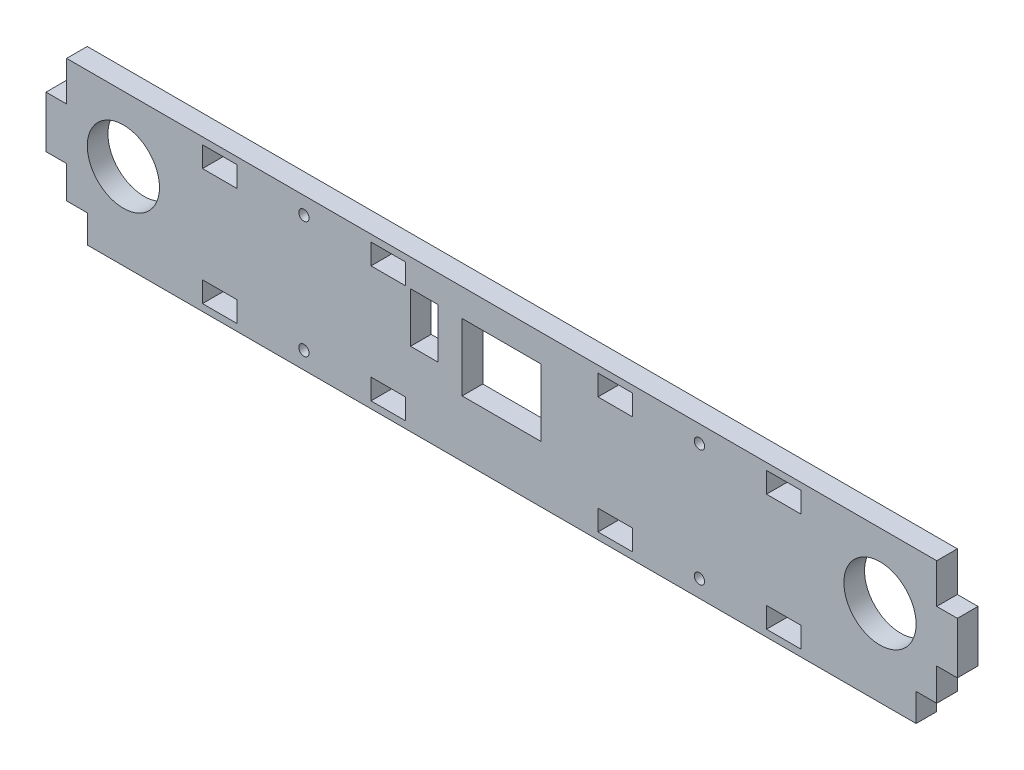
SolidWorks part; units mm, degrees
ref_plane "Front" through (0, 0, 0) normal (0, 0, 1) x (1, 0, 0)
ref_plane "Top" through (0, 0, 0) normal (0, 1, 0) x (1, 0, 0)
ref_plane "Right" through (0, 0, 0) normal (1, 0, 0) x (0, 0, -1)
sketch "Эскиз1" plane through (0, 0, 0) normal (0, 0, 1) x (1, 0, 0)
  line L0 (28, 20) -> (38, 20)
  line L1 (28, 14) -> (28, 20)
  line L2 (38, 14) -> (28, 14)
  line L3 (38, 20) -> (38, 14)
  line L4 (87, 20) -> (87, 14)
  line L5 (77, 20) -> (87, 20)
  line L6 (77, 14) -> (77, 20)
  line L7 (87, 14) -> (77, 14)
  line L8 (28, -20) -> (28, -14)
  line L9 (38, -20) -> (28, -20)
  line L10 (38, -14) -> (38, -20)
  line L11 (28, -14) -> (38, -14)
  line L12 (87, -20) -> (77, -20)
  line L13 (87, -14) -> (87, -20)
  line L14 (77, -14) -> (87, -14)
  line L15 (77, -20) -> (77, -14)
  line L16 (-38, 14) -> (-28, 14)
  line L17 (-28, 14) -> (-28, 20)
  line L18 (-28, 20) -> (-38, 20)
  line L19 (-38, 20) -> (-38, 14)
  line L20 (-77, 14) -> (-77, 20)
  line L21 (-77, 20) -> (-87, 20)
  line L22 (-87, 20) -> (-87, 14)
  line L23 (-87, 14) -> (-77, 14)
  line L24 (-126.5, 22) -> (-126.5, 10.5)
  line L25 (126.5, 22) -> (126.5, 10.5)
  line L26 (126.5, 10.5) -> (132.5, 10.5)
  line L27 (132.5, 10.5) -> (132.5, -4.5)
  line L28 (132.5, -4.5) -> (126.5, -4.5)
  line L29 (126.5, -4.5) -> (126.5, -13.9)
  line L30 (126.5, -13.9) -> (120.5, -13.9)
  line L31 (120.5, -13.9) -> (120.5, -22)
  line L32 (-120.5, -13.9) -> (-120.5, -22)
  line L33 (-126.5, -13.9) -> (-120.5, -13.9)
  line L34 (-126.5, -4.5) -> (-126.5, -13.9)
  line L35 (-132.5, -4.5) -> (-126.5, -4.5)
  line L36 (-132.5, 10.5) -> (-132.5, -4.5)
  line L37 (-126.5, 10.5) -> (-132.5, 10.5)
  line L38 (-38, -14) -> (-38, -20)
  line L39 (-38, -20) -> (-28, -20)
  line L40 (-28, -20) -> (-28, -14)
  line L41 (-28, -14) -> (-38, -14)
  line L42 (-77, -14) -> (-87, -14)
  line L43 (-87, -14) -> (-87, -20)
  line L44 (-87, -20) -> (-77, -20)
  line L45 (-77, -20) -> (-77, -14)
  line L46 (120.5, -22) -> (-120.5, -22)
  line L47 (126.5, 22) -> (-126.5, 22)
  line L48 (-18.5, -0.5) -> (-18.5, 14)
  line L49 (-18.5, 14) -> (-26.5, 14)
  line L50 (-26.5, 14) -> (-26.5, -0.5)
  line L51 (-26.5, -0.5) -> (-18.5, -0.5)
  line L52 (-11.5, -5.5) -> (-11.5, 14)
  line L53 (11.5, -5.5) -> (11.5, 14)
  line L54 (11.5, 14) -> (-11.5, 14)
  line L55 (-11.5, -5.5) -> (11.5, -5.5)
  circle A0 centre (57.5, 17) radius 1.5
  circle A1 centre (110, 3) radius 10.5
  circle A2 centre (57.5, -17) radius 1.5
  circle A3 centre (-57.5, 17) radius 1.5
  circle A4 centre (-110, 3) radius 10.5
  circle A5 centre (-57.5, -17) radius 1.5
extrude "Бобышка-Вытянуть1" add sketch "Эскиз1" along normal blind 6
